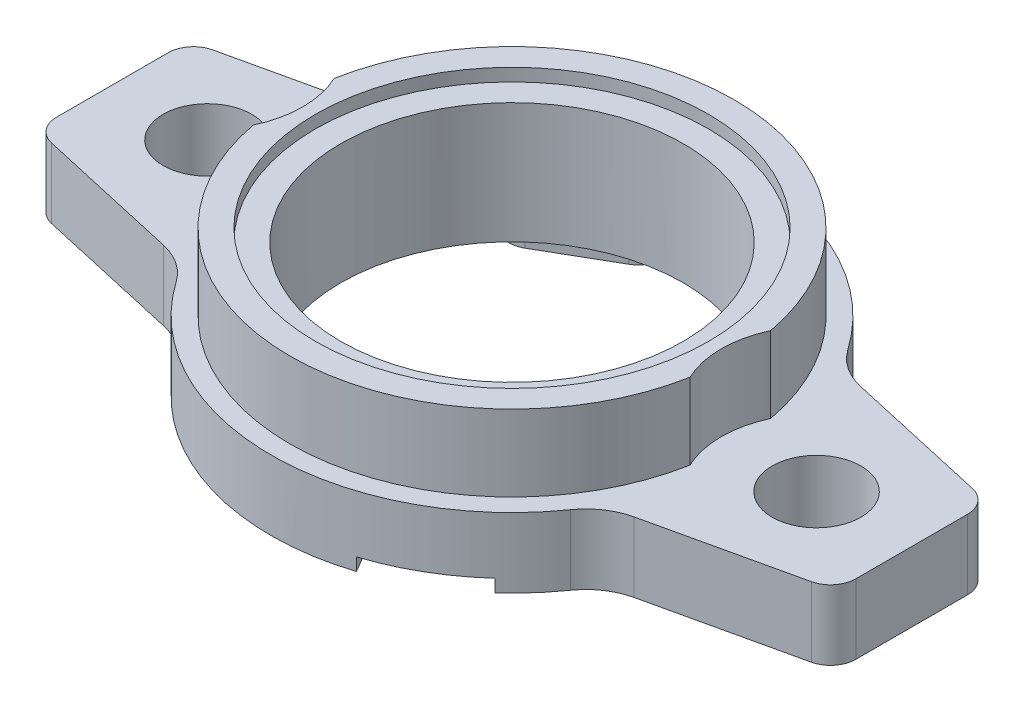
SolidWorks part; units mm, degrees
material "Простая углеродистая сталь"
ref_plane "Спереди" through (0, 0, 0) normal (0, 0, 1) x (1, 0, 0)
ref_plane "Сверху" through (0, 0, 0) normal (0, 1, 0) x (1, 0, 0)
ref_plane "Справа" through (0, 0, 0) normal (1, 0, 0) x (0, 0, -1)
sketch "Эскиз1" plane through (0, 0, 0) normal (0, 1, 0) x (1, 0, 0)
  line L0 (-1000, 0) -> (49000, 0) construction
  line L1 (0, -1000) -> (0, 49000) construction
  line L2 (-31.5, 4.4) -> (-31.5, -4.4)
  line L3 (-29.939, 6.3512) -> (-16.5298, 9.3683)
  line L4 (-29.939, -6.3512) -> (-16.5298, -9.3683)
  line L5 (29.939, -6.3512) -> (16.5298, -9.3683)
  line L6 (29.939, 6.3512) -> (16.5298, 9.3683)
  line L7 (31.5, 4.4) -> (31.5, -4.4)
  circle A0 centre (0, 0) radius 19
  circle A1 centre (-24, 0) radius 3.5
  circle A2 centre (-24, 0) radius 7.5 construction
  arc A3 (-31.5, -4.4) -> (-29.939, -6.3512) centre (-29.5, -4.4) ccw
  arc A4 (-31.5, 4.4) -> (-29.939, 6.3512) centre (-29.5, 4.4) cw
  circle A5 centre (24, 0) radius 7.5 construction
  arc A6 (31.5, 4.4) -> (29.939, 6.3512) centre (29.5, 4.4) ccw
  arc A7 (31.5, -4.4) -> (29.939, -6.3512) centre (29.5, -4.4) cw
  circle A8 centre (24, 0) radius 3.5
  point P16 (-31.5, -6)
  point P19 (-31.5, 6)
  dimension "D1" = 38
  dimension "D3" = 7
  dimension "D4" = 15
  dimension "D6" = 2
  dimension "D2" = 48
  dimension "D5" = 12
extrude "Бобышка-Вытянуть1" add sketch "Эскиз1" along normal blind 11.5 contours A4 L2 A3 L4 A0 L3 A1 | A0 | A7 L7 A6 L6 A0 L5 A8
sketch "Эскиз2" plane through (0, 11.5, 0) normal (0, 1, 0) x (1, 0, 0)
  arc A0 (17.2083, 3.1817) -> (-17.2083, 3.1817) centre (0, 0) ccw
  arc A1 (16.5298, 9.3683) -> (-16.5298, 9.3683) centre (0, 0) ccw construction
  circle A2 centre (0, 0) radius 42.1139
  arc A3 (-17.2083, -3.1817) -> (-17.2083, 3.1817) centre (-24, 0) ccw
  arc A4 (17.2083, 3.1817) -> (17.2083, -3.1817) centre (24, 0) ccw
  arc A5 (-17.2083, -3.1817) -> (17.2083, -3.1817) centre (0, 0) ccw
  dimension "D1" = 1.5
extrude "Вырез-Вытянуть1" cut sketch "Эскиз2" against normal blind 6
sketch "Эскиз3" plane through (0, 11.5, 0) normal (0, 1, 0) x (1, 0, 0)
  circle A0 centre (0, 0) radius 15.5
  arc A1 (17.2083, 3.1817) -> (-17.2083, 3.1817) centre (0, 0) ccw construction
  dimension "D1" = 2
extrude "Вырез-Вытянуть3" cut sketch "Эскиз3" against normal blind 1
sketch "Эскиз4" plane through (0, 0, 0) normal (0, -1, 0) x (1, 0, 0)
  line L0 (-20.8486, -5.3216) -> (-15.7182, -6.4759)
  line L1 (-29.939, -6.3512) -> (-16.5298, -9.3683) construction
  line L2 (0, -1000) -> (0, 49000) construction
  line L3 (-1000, 0) -> (49000, 0) construction
  line L4 (-20.8486, 5.3216) -> (-15.7182, 6.4759)
  line L5 (20.8486, 5.3216) -> (15.7182, 6.4759)
  line L6 (20.8486, -5.3216) -> (15.7182, -6.4759)
  line L7 (0, 0) -> (25000, 43301.2702) construction
  line L9 (6.0359, 18.4545) -> (12.9641, 14.4545)
  line L10 (6.0359, 18.4545) -> (4.5359, 15.8564)
  line L11 (4.9019, 14.4904) -> (10.0981, 11.4904)
  line L12 (12.9641, 14.4545) -> (11.4641, 11.8564)
  line L13 (6.0359, 18.4545) -> (10.9641, 10.9904) construction
  line L14 (4.0359, 14.9904) -> (12.9641, 14.4545) construction
  line L15 (4.4019, 13.6244) -> (9.5981, 10.6244)
  line L18 (-0.2068, 0.1194) -> (-43301.477, 25000.1194) construction
  line L19 (5.6699, 19.8205) -> (3.6699, 16.3564) construction
  line L20 (5.6699, 19.8205) -> (14.3301, 14.8205) construction
  line L21 (14.3301, 14.8205) -> (12.3301, 11.3564) construction
  line L22 (-10.9641, -10.9904) -> (-6.0359, -18.4545) construction
  line L23 (-12.9641, -14.4545) -> (-4.0359, -14.9904) construction
  line L25 (-9.5981, -10.6244) -> (-4.4019, -13.6244)
  line L26 (-6.0359, -18.4545) -> (-4.5359, -15.8564)
  line L27 (-10.0981, -11.4904) -> (-4.9019, -14.4904)
  line L28 (-12.9641, -14.4545) -> (-11.4641, -11.8564)
  line L29 (-12.9641, -14.4545) -> (-6.0359, -18.4545)
  arc A0 (-15.7182, -6.4759) -> (-13.2561, -10.6432) centre (0, 0) ccw
  arc A1 (16.5298, 9.3683) -> (-16.5298, 9.3683) centre (0, 0) ccw construction
  arc A2 (-21.242, -3.5558) -> (-21.242, 3.5558) centre (-24, 0) ccw
  circle A3 centre (-24, 0) radius 3.5 construction
  arc A4 (21.242, 3.5558) -> (21.242, -3.5558) centre (24, 0) ccw
  arc A5 (10.0981, 11.4904) -> (11.4641, 11.8564) centre (10.5981, 12.3564) ccw
  arc A6 (20.8486, -5.3216) -> (21.242, -3.5558) centre (20.6291, -4.3459) ccw
  arc A7 (20.8486, 5.3216) -> (21.242, 3.5558) centre (20.6291, 4.3459) cw
  arc A8 (-20.8486, -5.3216) -> (-21.242, -3.5558) centre (-20.6291, -4.3459) cw
  arc A9 (-20.8486, 5.3216) -> (-21.242, 3.5558) centre (-20.6291, 4.3459) ccw
  arc A10 (15.7182, 6.4759) -> (13.2561, 10.6432) centre (0, 0) ccw
  arc A11 (4.5359, 15.8564) -> (4.9019, 14.4904) centre (5.4019, 15.3564) ccw
  arc A12 (3.4253, 15.661) -> (4.4019, 13.6244) centre (5.4019, 15.3564) ccw
  arc A13 (9.5981, 10.6244) -> (11.8502, 10.7969) centre (10.5981, 12.3564) ccw
  arc A14 (2.5892, 16.8017) -> (-15.7182, 6.4759) centre (0, 0) ccw
  arc A15 (-4.4019, -13.6244) -> (-3.4253, -15.661) centre (-5.4019, -15.3564) cw
  arc A16 (-11.8502, -10.7969) -> (-9.5981, -10.6244) centre (-10.5981, -12.3564) cw
  arc A17 (-11.4641, -11.8564) -> (-10.0981, -11.4904) centre (-10.5981, -12.3564) cw
  arc A18 (-4.9019, -14.4904) -> (-4.5359, -15.8564) centre (-5.4019, -15.3564) cw
  arc A19 (3.4253, 15.661) -> (2.5892, 16.8017) centre (2.4369, 15.8133) ccw
  arc A20 (-2.5892, -16.8017) -> (15.7182, -6.4759) centre (0, 0) ccw
  arc A21 (11.8502, 10.7969) -> (13.2561, 10.6432) centre (12.4763, 10.0171) cw
  arc A22 (3.6699, 16.3564) -> (4.4019, 13.6244) centre (5.4019, 15.3564) ccw construction
  arc A23 (-11.8502, -10.7969) -> (-13.2561, -10.6432) centre (-12.4763, -10.0171) cw
  arc A24 (9.5981, 10.6244) -> (12.3301, 11.3564) centre (10.5981, 12.3564) ccw construction
  arc A25 (-3.4253, -15.661) -> (-2.5892, -16.8017) centre (-2.4369, -15.8133) ccw
  point P1 (8.5, 14.7224)
  point P14 (24.9878, -4.3902)
  point P31 (24.9878, 4.3902)
  point P34 (-24.9878, -4.3902)
  point P37 (-24.9878, 4.3902)
  point P74 (-8.5, -14.7224)
  dimension "D1" = 2
  dimension "D2" = 1
  dimension "D3" = 1
  dimension "D7" = 1
  dimension "D9" = 2
  dimension "D4" = 30
  dimension "D5" = 4
  dimension "D6" = 8
  dimension "D8" = 1
extrude "Вырез-Вытянуть4" cut sketch "Эскиз4" against normal blind 1
fillet "Скругление1" radius 5 4 edges at (16.5298, 2.75, -9.3683) (-16.5298, 2.75, -9.3683) (-16.5298, 2.75, 9.3683) (16.5298, 2.75, 9.3683)
sketch "Эскиз5" plane through (0, 10.5, 0) normal (0, 1, 0) x (1, 0, 0)
  circle A0 centre (0, 0) radius 13.5
  circle A1 centre (0, 0) radius 15.5 construction
  dimension "D1" = 2
extrude "Вырез-Вытянуть6" cut sketch "Эскиз5" against normal blind 21
